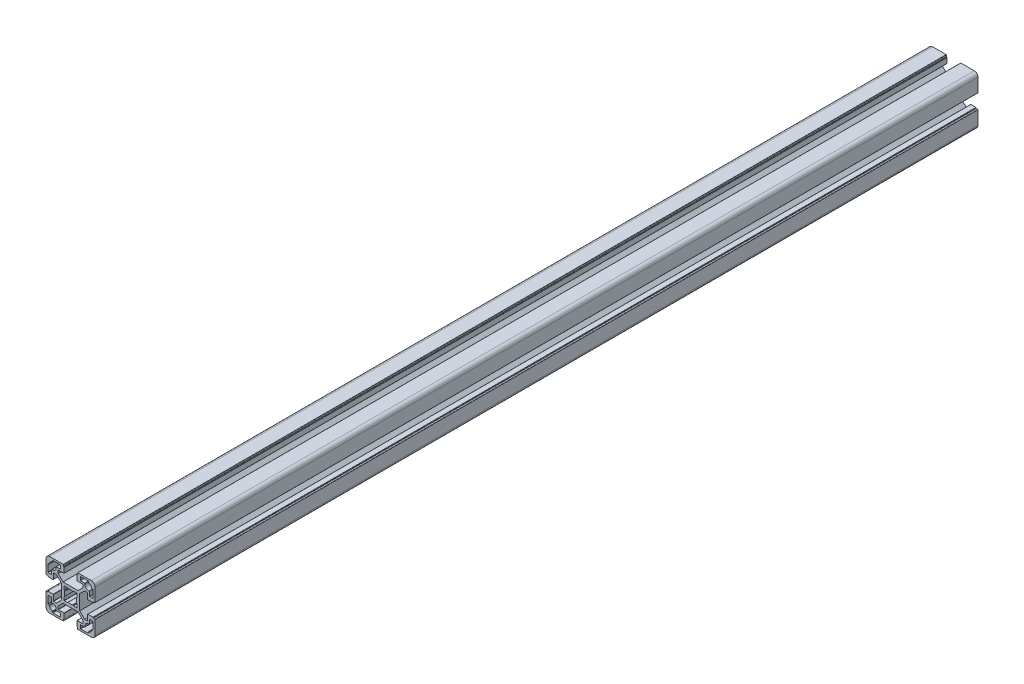
SolidWorks part; units mm, degrees
material "3.1355 (EN-AW 2024)"
ref_plane "Спереди" through (0, 0, 0) normal (0, 0, 1) x (1, 0, 0)
ref_plane "Сверху" through (0, 0, 0) normal (0, 1, 0) x (1, 0, 0)
ref_plane "Справа" through (0, 0, 0) normal (1, 0, 0) x (0, 0, -1)
sketch "Model" plane through (0, 0, 0) normal (0, 0, 1) x (1, 0, 0)
  line L0 (15.7, -8) -> (18.3, -8)
  line L1 (18.5, -8.2) -> (18.5, -14.3)
  line L2 (18.3, -14.5) -> (17.4432, -14.5)
  line L3 (14.5, -17.4432) -> (14.5, -18.3)
  line L4 (14.3, -18.5) -> (8.2, -18.5)
  line L5 (8, -18.3) -> (8, -15.7)
  line L6 (8.2, -15.5) -> (11.55, -15.5)
  line L7 (11.75, -15.3) -> (11.75, -14.5)
  line L8 (14.5, -11.75) -> (15.3, -11.75)
  line L9 (15.5, -11.55) -> (15.5, -8.2)
  line L10 (-18.3, -8) -> (-15.7, -8)
  line L11 (-15.5, -8.2) -> (-15.5, -11.55)
  line L12 (-15.3, -11.75) -> (-14.5, -11.75)
  line L13 (-11.75, -14.5) -> (-11.75, -15.3)
  line L14 (-11.55, -15.5) -> (-8.2, -15.5)
  line L15 (-8, -15.7) -> (-8, -18.3)
  line L16 (-8.2, -18.5) -> (-14.3, -18.5)
  line L17 (-14.5, -18.3) -> (-14.5, -17.4432)
  line L18 (-17.4432, -14.5) -> (-18.3, -14.5)
  line L19 (-18.5, -14.3) -> (-18.5, -8.2)
  line L20 (-5, 5.2) -> (-2.261, 5.2)
  line L21 (-2.261, 5.2) -> (-2.0719, 4.7652)
  line L22 (2.0719, 4.7652) -> (2.261, 5.2)
  line L23 (2.261, 5.2) -> (5, 5.2)
  line L24 (5.2, 5) -> (5.2, 2.261)
  line L25 (5.2, 2.261) -> (4.7652, 2.0719)
  line L26 (4.7652, -2.0719) -> (5.2, -2.261)
  line L27 (5.2, -2.261) -> (5.2, -5)
  line L28 (5, -5.2) -> (2.261, -5.2)
  line L29 (2.261, -5.2) -> (2.0719, -4.7652)
  line L30 (-2.0719, -4.7652) -> (-2.261, -5.2)
  line L31 (-2.261, -5.2) -> (-5, -5.2)
  line L32 (-5.2, -5) -> (-5.2, -2.261)
  line L33 (-5.2, -2.261) -> (-4.7652, -2.0719)
  line L34 (-4.7652, 2.0719) -> (-5.2, 2.261)
  line L35 (-5.2, 2.261) -> (-5.2, 5)
  line L36 (11.55, 15.5) -> (8.2, 15.5)
  line L37 (8, 15.7) -> (8, 18.3)
  line L38 (8.2, 18.5) -> (14.3, 18.5)
  line L39 (14.5, 18.3) -> (14.5, 17.4432)
  line L40 (17.4432, 14.5) -> (18.3, 14.5)
  line L41 (18.5, 14.3) -> (18.5, 8.2)
  line L42 (18.3, 8) -> (15.7, 8)
  line L43 (15.5, 8.2) -> (15.5, 11.55)
  line L44 (15.3, 11.75) -> (14.5, 11.75)
  line L45 (11.75, 14.5) -> (11.75, 15.3)
  line L46 (-14.5, 11.75) -> (-15.3, 11.75)
  line L47 (-15.5, 11.55) -> (-15.5, 8.2)
  line L48 (-15.7, 8) -> (-18.3, 8)
  line L49 (-18.5, 8.2) -> (-18.5, 14.3)
  line L50 (-18.3, 14.5) -> (-17.4432, 14.5)
  line L51 (-14.5, 17.4432) -> (-14.5, 18.3)
  line L52 (-14.3, 18.5) -> (-8.2, 18.5)
  line L53 (-8, 18.3) -> (-8, 15.7)
  line L54 (-8.2, 15.5) -> (-11.55, 15.5)
  line L55 (-11.75, 15.3) -> (-11.75, 14.5)
  line L56 (7.5, 6.0858) -> (11.4642, 10.05)
  line L57 (11.4642, 10.05) -> (13.8, 10.05)
  line L58 (14, 9.85) -> (14, 5.35)
  line L59 (14.2, 5.15) -> (18.3, 5.15)
  line L60 (18.5, 5.35) -> (18.5, 5.6)
  line L61 (18.7, 5.8) -> (19.8, 5.8)
  line L62 (20, 6) -> (20, 17)
  line L63 (17, 20) -> (6, 20)
  line L64 (5.8, 19.8) -> (5.8, 18.7)
  line L65 (5.6, 18.5) -> (5.35, 18.5)
  line L66 (5.15, 18.3) -> (5.15, 14.2)
  line L67 (5.35, 14) -> (9.85, 14)
  line L68 (10.05, 13.8) -> (10.05, 11.4642)
  line L69 (10.05, 11.4642) -> (6.0858, 7.5)
  line L70 (6.0858, 7.5) -> (-6.0858, 7.5)
  line L71 (-6.0858, 7.5) -> (-10.05, 11.4642)
  line L72 (-10.05, 11.4642) -> (-10.05, 13.8)
  line L73 (-9.85, 14) -> (-5.35, 14)
  line L74 (-5.15, 14.2) -> (-5.15, 18.3)
  line L75 (-5.35, 18.5) -> (-5.6, 18.5)
  line L76 (-5.8, 18.7) -> (-5.8, 19.8)
  line L77 (-6, 20) -> (-17, 20)
  line L78 (-20, 17) -> (-20, 6)
  line L79 (-19.8, 5.8) -> (-18.7, 5.8)
  line L80 (-18.5, 5.6) -> (-18.5, 5.35)
  line L81 (-18.3, 5.15) -> (-14.2, 5.15)
  line L82 (-14, 5.35) -> (-14, 9.85)
  line L83 (-13.8, 10.05) -> (-11.4642, 10.05)
  line L84 (-11.4642, 10.05) -> (-7.5, 6.0858)
  line L85 (-7.5, 6.0858) -> (-7.5, -6.0858)
  line L86 (-7.5, -6.0858) -> (-11.4642, -10.05)
  line L87 (-11.4642, -10.05) -> (-13.8, -10.05)
  line L88 (-14, -9.85) -> (-14, -5.35)
  line L89 (-14.2, -5.15) -> (-18.3, -5.15)
  line L90 (-18.5, -5.35) -> (-18.5, -5.6)
  line L91 (-18.7, -5.8) -> (-19.8, -5.8)
  line L92 (-20, -6) -> (-20, -17)
  line L93 (-17, -20) -> (-6, -20)
  line L94 (-5.8, -19.8) -> (-5.8, -18.7)
  line L95 (-5.6, -18.5) -> (-5.35, -18.5)
  line L96 (-5.15, -18.3) -> (-5.15, -14.2)
  line L97 (-5.35, -14) -> (-9.85, -14)
  line L98 (-10.05, -13.8) -> (-10.05, -11.4642)
  line L99 (-10.05, -11.4642) -> (-6.0858, -7.5)
  line L100 (-6.0858, -7.5) -> (6.0858, -7.5)
  line L101 (6.0858, -7.5) -> (10.05, -11.4642)
  line L102 (10.05, -11.4642) -> (10.05, -13.8)
  line L103 (9.85, -14) -> (5.35, -14)
  line L104 (5.15, -14.2) -> (5.15, -18.3)
  line L105 (5.35, -18.5) -> (5.6, -18.5)
  line L106 (5.8, -18.7) -> (5.8, -19.8)
  line L107 (6, -20) -> (17, -20)
  line L108 (20, -17) -> (20, -6)
  line L109 (19.8, -5.8) -> (18.7, -5.8)
  line L110 (18.5, -5.6) -> (18.5, -5.35)
  line L111 (18.3, -5.15) -> (14.2, -5.15)
  line L112 (14, -5.35) -> (14, -9.85)
  line L113 (13.8, -10.05) -> (11.4642, -10.05)
  line L114 (11.4642, -10.05) -> (7.5, -6.0858)
  line L115 (7.5, -6.0858) -> (7.5, 6.0858)
  arc A0 (15.7, -8) -> (15.5, -8.2) centre (15.7, -8.2) ccw
  arc A1 (18.5, -8.2) -> (18.3, -8) centre (18.3, -8.2) ccw
  arc A2 (18.3, -14.5) -> (18.5, -14.3) centre (18.3, -14.3) ccw
  arc A3 (17.4432, -14.5) -> (17.2437, -14.6864) centre (17.4432, -14.7) ccw
  arc A4 (14.6864, -17.2437) -> (17.2437, -14.6864) centre (14.5, -14.5) ccw
  arc A5 (14.6864, -17.2437) -> (14.5, -17.4432) centre (14.7, -17.4432) ccw
  arc A6 (14.3, -18.5) -> (14.5, -18.3) centre (14.3, -18.3) ccw
  arc A7 (8, -18.3) -> (8.2, -18.5) centre (8.2, -18.3) ccw
  arc A8 (8.2, -15.5) -> (8, -15.7) centre (8.2, -15.7) ccw
  arc A9 (11.55, -15.5) -> (11.75, -15.3) centre (11.55, -15.3) ccw
  arc A10 (14.5, -11.75) -> (11.75, -14.5) centre (14.5, -14.5) ccw
  arc A11 (15.3, -11.75) -> (15.5, -11.55) centre (15.3, -11.55) ccw
  arc A12 (-18.3, -8) -> (-18.5, -8.2) centre (-18.3, -8.2) ccw
  arc A13 (-15.5, -8.2) -> (-15.7, -8) centre (-15.7, -8.2) ccw
  arc A14 (-15.5, -11.55) -> (-15.3, -11.75) centre (-15.3, -11.55) ccw
  arc A15 (-11.75, -14.5) -> (-14.5, -11.75) centre (-14.5, -14.5) ccw
  arc A16 (-11.75, -15.3) -> (-11.55, -15.5) centre (-11.55, -15.3) ccw
  arc A17 (-8, -15.7) -> (-8.2, -15.5) centre (-8.2, -15.7) ccw
  arc A18 (-8.2, -18.5) -> (-8, -18.3) centre (-8.2, -18.3) ccw
  arc A19 (-14.5, -18.3) -> (-14.3, -18.5) centre (-14.3, -18.3) ccw
  arc A20 (-14.5, -17.4432) -> (-14.6864, -17.2437) centre (-14.7, -17.4432) ccw
  arc A21 (-17.2437, -14.6864) -> (-14.6864, -17.2437) centre (-14.5, -14.5) ccw
  arc A22 (-17.2437, -14.6864) -> (-17.4432, -14.5) centre (-17.4432, -14.7) ccw
  arc A23 (-18.5, -14.3) -> (-18.3, -14.5) centre (-18.3, -14.3) ccw
  arc A24 (-5, 5.2) -> (-5.2, 5) centre (-5, 5) ccw
  arc A25 (-2.0719, 4.7652) -> (-1.8159, 4.6586) centre (-1.8885, 4.8449) ccw
  arc A26 (1.8159, 4.6586) -> (-1.8159, 4.6586) centre (0, 0) ccw
  arc A27 (1.8159, 4.6586) -> (2.0719, 4.7652) centre (1.8885, 4.8449) ccw
  arc A28 (5.2, 5) -> (5, 5.2) centre (5, 5) ccw
  arc A29 (4.7652, 2.0719) -> (4.6586, 1.8159) centre (4.8449, 1.8885) ccw
  arc A30 (4.6586, -1.8159) -> (4.6586, 1.8159) centre (0, 0) ccw
  arc A31 (4.6586, -1.8159) -> (4.7652, -2.0719) centre (4.8449, -1.8885) ccw
  arc A32 (5, -5.2) -> (5.2, -5) centre (5, -5) ccw
  arc A33 (2.0719, -4.7652) -> (1.8159, -4.6586) centre (1.8885, -4.8449) ccw
  arc A34 (-1.8159, -4.6586) -> (1.8159, -4.6586) centre (0, 0) ccw
  arc A35 (-1.8159, -4.6586) -> (-2.0719, -4.7652) centre (-1.8885, -4.8449) ccw
  arc A36 (-5.2, -5) -> (-5, -5.2) centre (-5, -5) ccw
  arc A37 (-4.7652, -2.0719) -> (-4.6586, -1.8159) centre (-4.8449, -1.8885) ccw
  arc A38 (-4.6586, 1.8159) -> (-4.6586, -1.8159) centre (0, 0) ccw
  arc A39 (-4.6586, 1.8159) -> (-4.7652, 2.0719) centre (-4.8449, 1.8885) ccw
  arc A40 (11.75, 15.3) -> (11.55, 15.5) centre (11.55, 15.3) ccw
  arc A41 (8, 15.7) -> (8.2, 15.5) centre (8.2, 15.7) ccw
  arc A42 (8.2, 18.5) -> (8, 18.3) centre (8.2, 18.3) ccw
  arc A43 (14.5, 18.3) -> (14.3, 18.5) centre (14.3, 18.3) ccw
  arc A44 (14.5, 17.4432) -> (14.6864, 17.2437) centre (14.7, 17.4432) ccw
  arc A45 (17.2437, 14.6864) -> (14.6864, 17.2437) centre (14.5, 14.5) ccw
  arc A46 (17.2437, 14.6864) -> (17.4432, 14.5) centre (17.4432, 14.7) ccw
  arc A47 (18.5, 14.3) -> (18.3, 14.5) centre (18.3, 14.3) ccw
  arc A48 (18.3, 8) -> (18.5, 8.2) centre (18.3, 8.2) ccw
  arc A49 (15.5, 8.2) -> (15.7, 8) centre (15.7, 8.2) ccw
  arc A50 (15.5, 11.55) -> (15.3, 11.75) centre (15.3, 11.55) ccw
  arc A51 (11.75, 14.5) -> (14.5, 11.75) centre (14.5, 14.5) ccw
  arc A52 (-14.5, 11.75) -> (-11.75, 14.5) centre (-14.5, 14.5) ccw
  arc A53 (-15.3, 11.75) -> (-15.5, 11.55) centre (-15.3, 11.55) ccw
  arc A54 (-15.7, 8) -> (-15.5, 8.2) centre (-15.7, 8.2) ccw
  arc A55 (-18.5, 8.2) -> (-18.3, 8) centre (-18.3, 8.2) ccw
  arc A56 (-18.3, 14.5) -> (-18.5, 14.3) centre (-18.3, 14.3) ccw
  arc A57 (-17.4432, 14.5) -> (-17.2437, 14.6864) centre (-17.4432, 14.7) ccw
  arc A58 (-14.6864, 17.2437) -> (-17.2437, 14.6864) centre (-14.5, 14.5) ccw
  arc A59 (-14.6864, 17.2437) -> (-14.5, 17.4432) centre (-14.7, 17.4432) ccw
  arc A60 (-14.3, 18.5) -> (-14.5, 18.3) centre (-14.3, 18.3) ccw
  arc A61 (-8, 18.3) -> (-8.2, 18.5) centre (-8.2, 18.3) ccw
  arc A62 (-8.2, 15.5) -> (-8, 15.7) centre (-8.2, 15.7) ccw
  arc A63 (-11.55, 15.5) -> (-11.75, 15.3) centre (-11.55, 15.3) ccw
  arc A64 (14, 9.85) -> (13.8, 10.05) centre (13.8, 9.85) ccw
  arc A65 (14, 5.35) -> (14.2, 5.15) centre (14.2, 5.35) ccw
  arc A66 (18.3, 5.15) -> (18.5, 5.35) centre (18.3, 5.35) ccw
  arc A67 (18.7, 5.8) -> (18.5, 5.6) centre (18.7, 5.6) ccw
  arc A68 (19.8, 5.8) -> (20, 6) centre (19.8, 6) ccw
  arc A69 (20, 17) -> (17, 20) centre (17, 17) ccw
  arc A70 (6, 20) -> (5.8, 19.8) centre (6, 19.8) ccw
  arc A71 (5.6, 18.5) -> (5.8, 18.7) centre (5.6, 18.7) ccw
  arc A72 (5.35, 18.5) -> (5.15, 18.3) centre (5.35, 18.3) ccw
  arc A73 (5.15, 14.2) -> (5.35, 14) centre (5.35, 14.2) ccw
  arc A74 (10.05, 13.8) -> (9.85, 14) centre (9.85, 13.8) ccw
  arc A75 (-9.85, 14) -> (-10.05, 13.8) centre (-9.85, 13.8) ccw
  arc A76 (-5.35, 14) -> (-5.15, 14.2) centre (-5.35, 14.2) ccw
  arc A77 (-5.15, 18.3) -> (-5.35, 18.5) centre (-5.35, 18.3) ccw
  arc A78 (-5.8, 18.7) -> (-5.6, 18.5) centre (-5.6, 18.7) ccw
  arc A79 (-5.8, 19.8) -> (-6, 20) centre (-6, 19.8) ccw
  arc A80 (-17, 20) -> (-20, 17) centre (-17, 17) ccw
  arc A81 (-20, 6) -> (-19.8, 5.8) centre (-19.8, 6) ccw
  arc A82 (-18.5, 5.6) -> (-18.7, 5.8) centre (-18.7, 5.6) ccw
  arc A83 (-18.5, 5.35) -> (-18.3, 5.15) centre (-18.3, 5.35) ccw
  arc A84 (-14.2, 5.15) -> (-14, 5.35) centre (-14.2, 5.35) ccw
  arc A85 (-13.8, 10.05) -> (-14, 9.85) centre (-13.8, 9.85) ccw
  arc A86 (-14, -9.85) -> (-13.8, -10.05) centre (-13.8, -9.85) ccw
  arc A87 (-14, -5.35) -> (-14.2, -5.15) centre (-14.2, -5.35) ccw
  arc A88 (-18.3, -5.15) -> (-18.5, -5.35) centre (-18.3, -5.35) ccw
  arc A89 (-18.7, -5.8) -> (-18.5, -5.6) centre (-18.7, -5.6) ccw
  arc A90 (-19.8, -5.8) -> (-20, -6) centre (-19.8, -6) ccw
  arc A91 (-20, -17) -> (-17, -20) centre (-17, -17) ccw
  arc A92 (-6, -20) -> (-5.8, -19.8) centre (-6, -19.8) ccw
  arc A93 (-5.6, -18.5) -> (-5.8, -18.7) centre (-5.6, -18.7) ccw
  arc A94 (-5.35, -18.5) -> (-5.15, -18.3) centre (-5.35, -18.3) ccw
  arc A95 (-5.15, -14.2) -> (-5.35, -14) centre (-5.35, -14.2) ccw
  arc A96 (-10.05, -13.8) -> (-9.85, -14) centre (-9.85, -13.8) ccw
  arc A97 (9.85, -14) -> (10.05, -13.8) centre (9.85, -13.8) ccw
  arc A98 (5.35, -14) -> (5.15, -14.2) centre (5.35, -14.2) ccw
  arc A99 (5.15, -18.3) -> (5.35, -18.5) centre (5.35, -18.3) ccw
  arc A100 (5.8, -18.7) -> (5.6, -18.5) centre (5.6, -18.7) ccw
  arc A101 (5.8, -19.8) -> (6, -20) centre (6, -19.8) ccw
  arc A102 (17, -20) -> (20, -17) centre (17, -17) ccw
  arc A103 (20, -6) -> (19.8, -5.8) centre (19.8, -6) ccw
  arc A104 (18.5, -5.6) -> (18.7, -5.8) centre (18.7, -5.6) ccw
  arc A105 (18.5, -5.35) -> (18.3, -5.15) centre (18.3, -5.35) ccw
  arc A106 (14.2, -5.15) -> (14, -5.35) centre (14.2, -5.35) ccw
  arc A107 (13.8, -10.05) -> (14, -9.85) centre (13.8, -9.85) ccw
  dimension "D1" = 40
extrude "База" add sketch "Model" against normal mid plane 720
